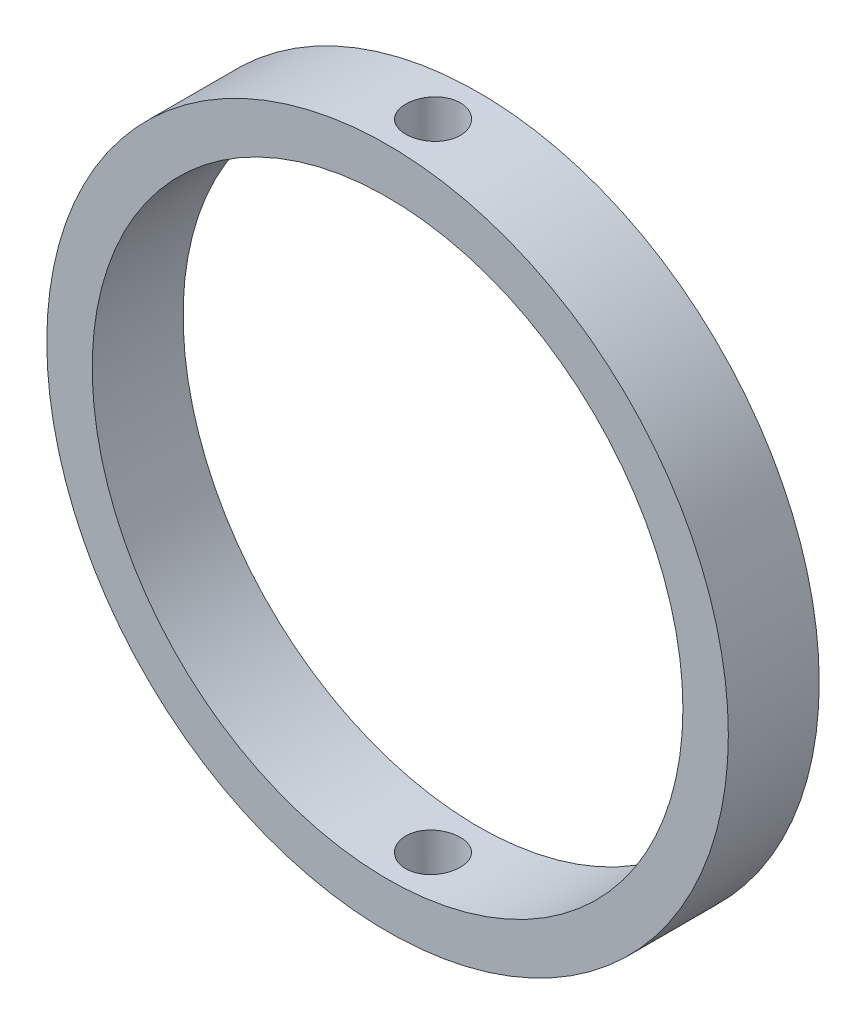
SolidWorks part; units mm, degrees
ref_plane "前视基准面" through (0, 0, 0) normal (0, 0, 1) x (1, 0, 0)
ref_plane "上视基准面" through (0, 0, 0) normal (0, 1, 0) x (1, 0, 0)
ref_plane "右视基准面" through (0, 0, 0) normal (1, 0, 0) x (0, 0, -1)
sketch "Sketch1" plane through (0, 0, 0) normal (0, 0, 1) x (1, 0, 0)
  circle A0 centre (0, 0) radius 41.275
  circle A1 centre (0, 0) radius 47.625
  dimension "D1" = 82.55
  dimension "D2" = 95.25
extrude "Boss-Extrude1" add sketch "Sketch1" along normal blind 12.7
ref_plane "Plane1" through (0, 47.625, 0) normal (0, 1, 0) x (1, 0, 0)
sketch "Sketch2" plane through (0, 47.625, 0) normal (0, 1, 0) x (1, 0, 0)
  line L0 (0, 0) -> (0, -12.7) construction
  line L1 (-47.625, -12.7) -> (47.625, -12.7) construction
  line L2 (41.275, 0) -> (-41.275, 0) construction
  circle A0 centre (0, -6.35) radius 3.81
  point P2 (0, 0)
  point P10 (0, 0)
  dimension "D1" = 7.62
extrude "Cut-Extrude1" cut sketch "Sketch2" against normal up to surface (6.35 mm away)
mirror "Mirror1" about plane through (0, 0, 0) normal (0, 1, 0) of "Cut-Extrude1"
